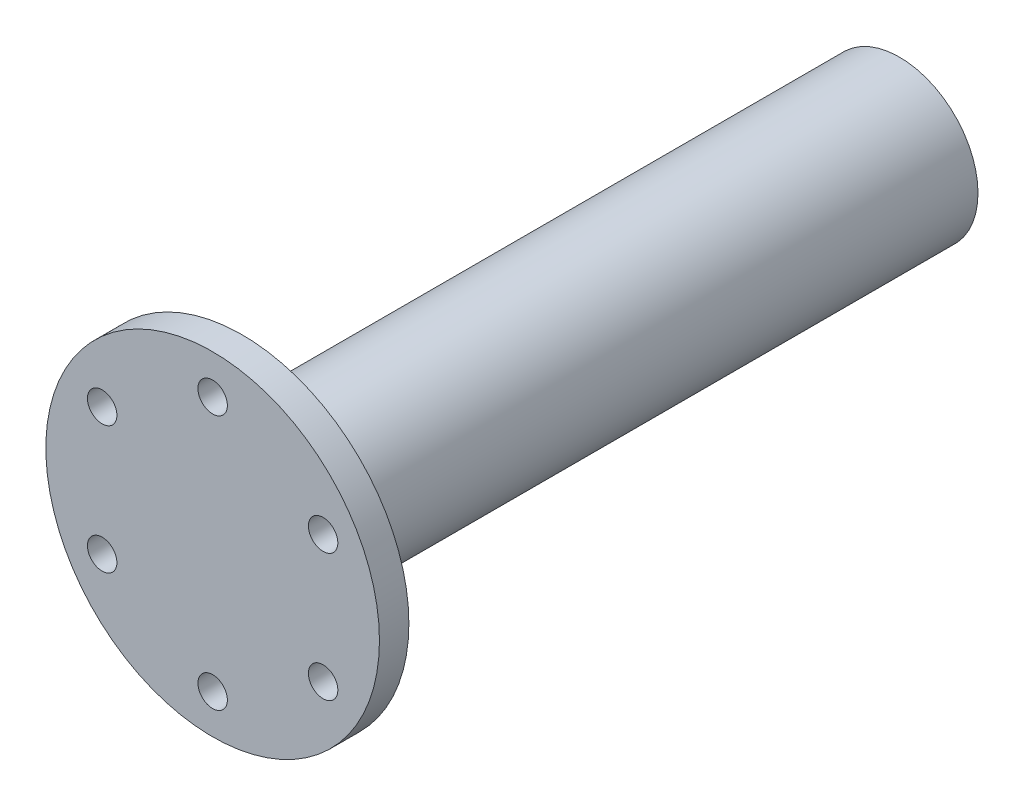
SolidWorks part; units mm, degrees
ref_plane "Front Plane" through (0, 0, 0) normal (0, 0, 1) x (1, 0, 0)
ref_plane "Top Plane" through (0, 0, 0) normal (0, 1, 0) x (1, 0, 0)
ref_plane "Right Plane" through (0, 0, 0) normal (1, 0, 0) x (0, 0, -1)
sketch "Croquis1" plane through (0, 0, 0) normal (0, 0, 1) x (1, 0, 0)
  circle A0 centre (0, 0) radius 8
extrude "Saliente-Extruir1" add sketch "Croquis1" along normal blind 67
sketch "Croquis2" plane through (0, 0, 67) normal (0, 0, 1) x (1, 0, 0)
  circle A0 centre (0, 0) radius 17
extrude "Saliente-Extruir2" add sketch "Croquis2" along normal blind 3
sketch "Croquis3" plane through (0, 0, 67) normal (0, 0, -1) x (-1, 0, 0)
  circle A0 centre (0, 0) radius 9
extrude "Saliente-Extruir3" add sketch "Croquis3" along normal blind 5 draft 23
sketch "Croquis4" plane through (0, 0, 70) normal (0, 0, 1) x (1, 0, 0)
  circle A1 centre (0, 13) radius 1.5
  circle A2 centre (11.2583, 6.5) radius 1.5
  circle A3 centre (11.2583, -6.5) radius 1.5
  circle A4 centre (0, -13) radius 1.5
  circle A5 centre (-11.2583, -6.5) radius 1.5
  circle A6 centre (-11.2583, 6.5) radius 1.5
  point P14 (0, 0)
  dimension "D1" = 6
extrude "Cortar-Extruir2" cut sketch "Croquis4" against normal blind 5
